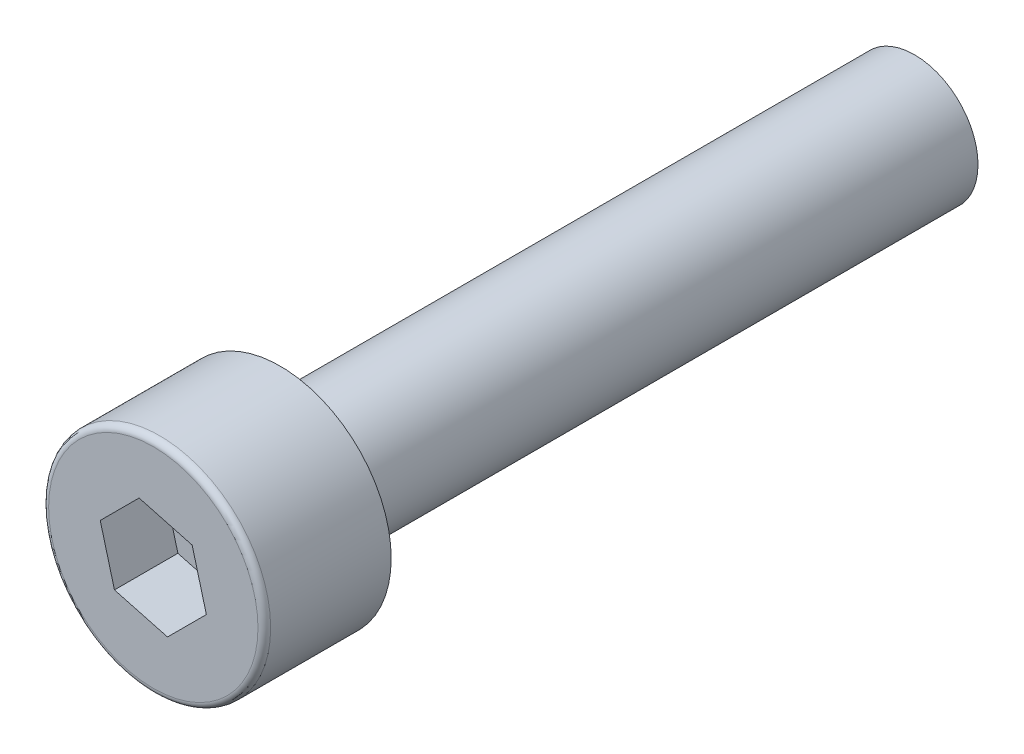
SolidWorks part; units mm, degrees
ref_plane "前视基准面" through (0, 0, 0) normal (0, 0, 1) x (1, 0, 0)
ref_plane "上视基准面" through (0, 0, 0) normal (0, 1, 0) x (1, 0, 0)
ref_plane "右视基准面" through (0, 0, 0) normal (1, 0, 0) x (0, 0, -1)
sketch "草图1" plane through (0, 0, 0) normal (0, 0, 1) x (1, 0, 0)
  circle A0 centre (0, 0) radius 3.5
  dimension "D1" = 7
extrude "凸台-拉伸1" add sketch "草图1" along normal blind 4
sketch "草图2" plane through (0, 0, 4) normal (0, 0, 1) x (1, 0, 0)
  line L1 (-1.2247, -1.2247) -> (0.4483, -1.673)
  line L2 (0.4483, -1.673) -> (1.673, -0.4483)
  line L3 (1.673, -0.4483) -> (1.2247, 1.2247)
  line L4 (1.2247, 1.2247) -> (-0.4483, 1.673)
  line L5 (-0.4483, 1.673) -> (-1.673, 0.4483)
  line L6 (-1.673, 0.4483) -> (-1.2247, -1.2247)
  circle A0 centre (0, 0) radius 1.5 construction
  dimension "D1" = 3
extrude "切除-拉伸1" cut sketch "草图2" against normal blind 2
sketch "草图3" plane through (0, 0, 0) normal (0, 0, -1) x (-1, 0, 0)
  circle A0 centre (0, 0) radius 2
  dimension "D1" = 4
extrude "凸台-拉伸2" add sketch "草图3" along normal blind 20
fillet "圆角1" radius 0.2 1 edges at (3.5, 0, 4)
